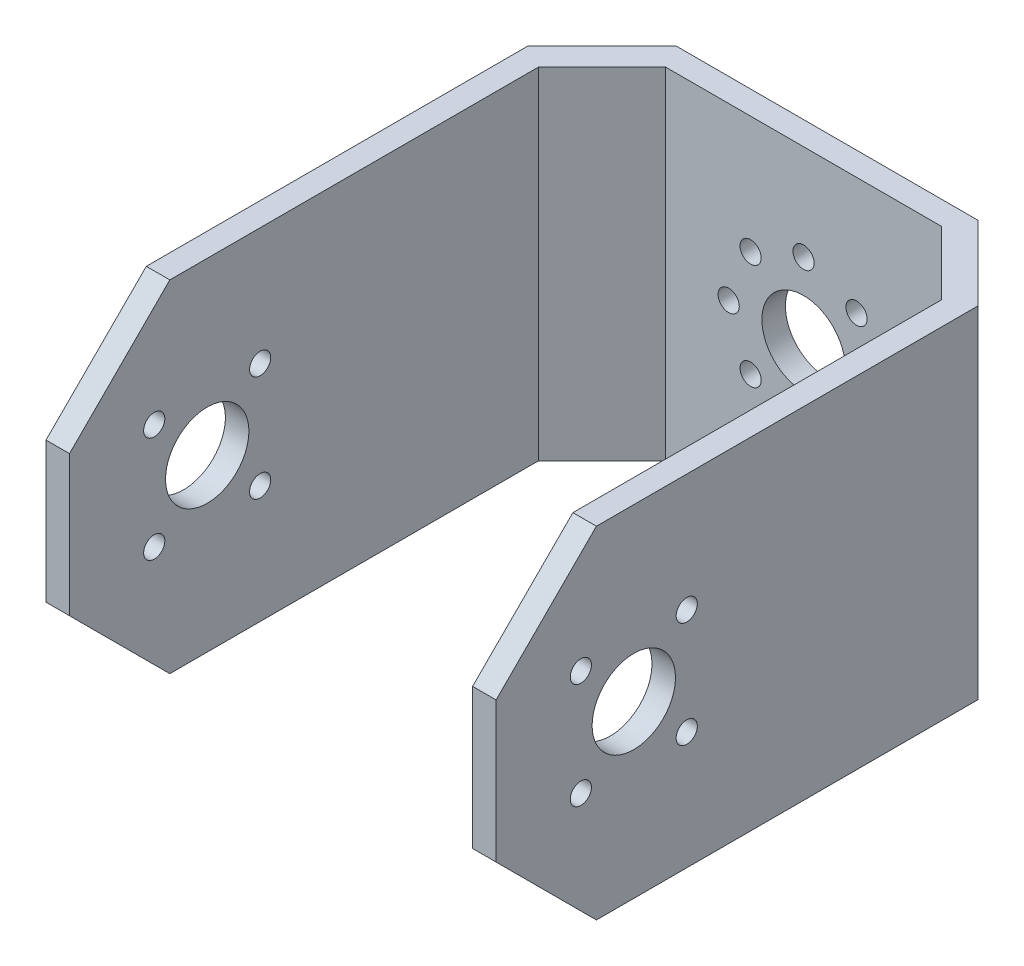
SolidWorks part; units mm, degrees
ref_plane "Front Plane" through (0, 0, 0) normal (0, 0, 1) x (1, 0, 0)
ref_plane "Top Plane" through (0, 0, 0) normal (0, 1, 0) x (1, 0, 0)
ref_plane "Right Plane" through (0, 0, 0) normal (1, 0, 0) x (0, 0, -1)
sketch "Sketch1" plane through (0, 0, 0) normal (0, 1, 0) x (1, 0, 0)
  line L0 (0, 0) -> (-21.25, 0)
  line L1 (-21.25, 0) -> (-21.25, -52.5)
  line L2 (-21.25, -52.5) -> (-19.03, -52.5)
  line L3 (-19.03, -52.5) -> (-19.03, -2.22)
  line L4 (-19.03, -2.22) -> (0, -2.22)
  line L5 (0, -2.22) -> (0, 0)
  dimension "D1" = 2.22
  dimension "D2" = 2.22
  dimension "D3" = 21.25
  dimension "D4" = 52.5
extrude "Boss-Extrude1" add sketch "Sketch1" along normal mid plane 32.2
sketch "Sketch2" plane through (-21.25, 0, 0) normal (-1, 0, 0) x (0, 0, 1)
  line L0 (43.03, 16.1) -> (52.5, 6.63)
  line L1 (0, 16.1) -> (52.5, 16.1) construction
  line L2 (52.5, 16.1) -> (52.5, -16.1) construction
  line L3 (52.5, 6.63) -> (52.5, -6.63) construction
  line L4 (52.5, -6.63) -> (43.03, -16.1)
  line L5 (0, -16.1) -> (52.5, -16.1) construction
  line L6 (43.03, -16.1) -> (43.03, 16.1) construction
  line L7 (0, 0) -> (52.5, 0) construction
  line L8 (43.03, 16.1) -> (52.5, 16.1)
  line L9 (52.5, 16.1) -> (52.5, 6.63)
  line L10 (43.03, -16.1) -> (52.5, -16.1)
  line L11 (52.5, -16.1) -> (52.5, -6.63)
  point P11 (52.5, 0)
  dimension "D1" = 13.26
  dimension "D2" = 45
extrude "Cut-Extrude1" cut sketch "Sketch2" against normal blind 32.2
sketch "Sketch3" plane through (-21.25, 0, 0) normal (-1, 0, 0) x (0, 0, 1)
  line L0 (39.5, 12.25) -> (39.5, 0) construction
  line L1 (44.5, -5) -> (34.5, -5) construction
  line L2 (44.5, -5) -> (44.5, 5) construction
  line L3 (44.5, 5) -> (34.5, 5) construction
  line L4 (34.5, -5) -> (34.5, 5) construction
  line L5 (44.5, -5) -> (34.5, 5) construction
  line L6 (44.5, 5) -> (34.5, -5) construction
  line L7 (39.5, 0) -> (52.5, 0) construction
  line L8 (52.5, 6.63) -> (52.5, -6.63) construction
  circle A0 centre (39.5, 0) radius 3.935
  circle A1 centre (34.5, 5) radius 1
  circle A2 centre (44.5, 5) radius 1
  circle A3 centre (44.5, -5) radius 1
  circle A4 centre (34.5, -5) radius 1
  dimension "D1" = 7.87
  dimension "D3" = 2
  dimension "D2" = 45
  dimension "D4" = 10
  dimension "D5" = 13
extrude "Cut-Extrude2" cut sketch "Sketch3" against normal blind 32.2
mirror "Mirror1" about plane through (0, 16.1, 2.22) normal (-1, 0, 0) of "Cut-Extrude1", "Boss-Extrude1", "Cut-Extrude2"
sketch "Sketch4" plane through (0, 0, 2.22) normal (0, 0, 1) x (1, 0, 0)
  line L0 (0, 9.4948) -> (0, 0) construction
  line L1 (5, -5) -> (-5, -5) construction
  line L2 (5, -5) -> (5, 5) construction
  line L3 (5, 5) -> (-5, 5) construction
  line L4 (-5, -5) -> (-5, 5) construction
  line L5 (5, -5) -> (-5, 5) construction
  line L6 (5, 5) -> (-5, -5) construction
  line L7 (7.0711, 0) -> (0, 7.0711) construction
  line L8 (7.0711, 0) -> (0, -7.0711) construction
  line L9 (0, 7.0711) -> (-7.0711, 0) construction
  line L10 (0, -7.0711) -> (-7.0711, 0) construction
  line L11 (7.0711, 0) -> (-7.0711, 0) construction
  line L12 (0, 7.0711) -> (0, -7.0711) construction
  circle A0 centre (0, 0) radius 3.935
  circle A1 centre (-5, 5) radius 1
  circle A2 centre (5, 5) radius 1
  circle A3 centre (5, -5) radius 1
  circle A4 centre (-5, -5) radius 1
  circle A5 centre (-7.0711, 0) radius 1
  circle A6 centre (0, 7.0711) radius 1
  circle A7 centre (7.0711, 0) radius 1
  circle A8 centre (0, -7.0711) radius 1
  dimension "D1" = 7.87
  dimension "D3" = 2
  dimension "D6" = 10
  dimension "D2" = 45
  dimension "D4" = 10
  dimension "D5" = 45
extrude "Cut-Extrude3" cut sketch "Sketch4" against normal blind 32.2
chamfer "Chamfer1" distance 6 angle 45 2 edges at (19.03, 0, 2.22) (-19.03, 0, 2.22)
chamfer "Chamfer2" distance 7 angle 45 2 edges at (21.25, 0, 0) (-21.25, 0, 0)
